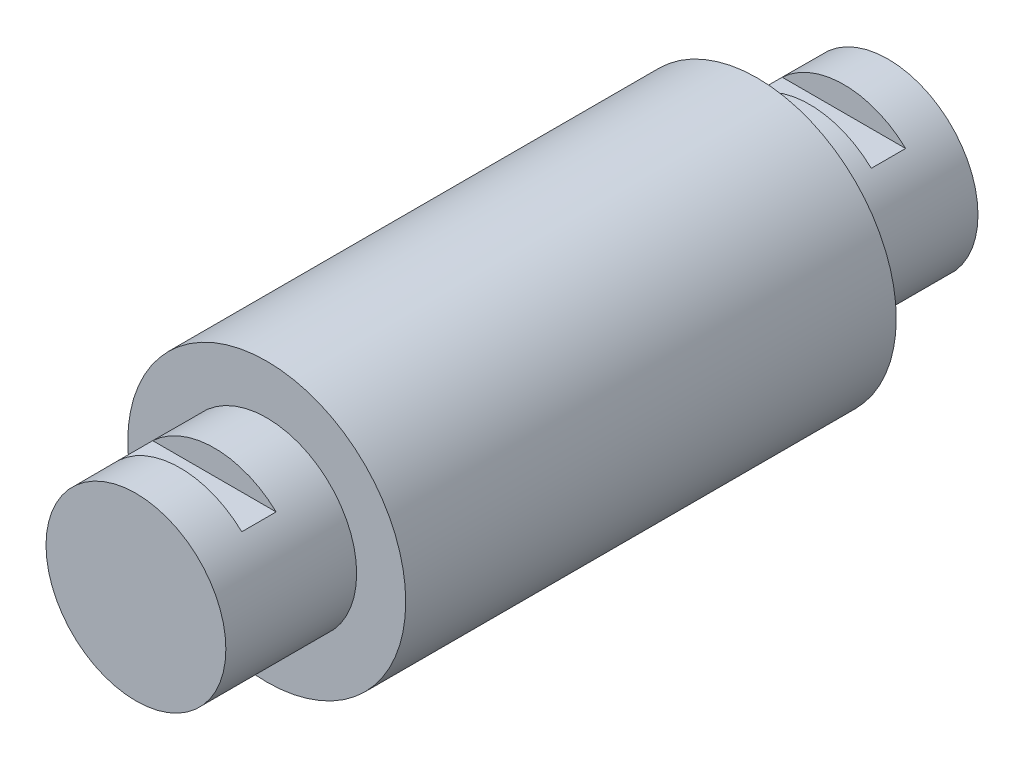
SolidWorks part; units mm, degrees
ref_plane "Front Plane" through (0, 0, 0) normal (0, 0, 1) x (1, 0, 0)
ref_plane "Top Plane" through (0, 0, 0) normal (0, 1, 0) x (1, 0, 0)
ref_plane "Right Plane" through (0, 0, 0) normal (1, 0, 0) x (0, 0, -1)
sketch "Sketch2" plane through (0, 0, 0) normal (0, 0, 1) x (1, 0, 0)
  circle A0 centre (0, 0) radius 42.5
  dimension "D1" = 85
extrude "Boss-Extrude2" add sketch "Sketch2" along normal mid plane 150 contours A0
sketch "Sketch3" plane through (0, 0, 75) normal (0, 0, 1) x (1, 0, 0)
  circle A0 centre (0, 0) radius 27.5
  dimension "D1" = 55
extrude "Boss-Extrude3" add sketch "Sketch3" along normal blind 40
sketch "Sketch4" plane through (0, 0, 0) normal (1, 0, 0) x (0, 0, -1)
  line L0 (-75, 27.5) -> (-115, 27.5) construction
  line L1 (-101.5, 28.7988) -> (-91, 28.7988)
  line L2 (-101.5, 28.7988) -> (-101.5, 20)
  line L3 (-101.5, 20) -> (-91, 20)
  line L4 (-91, 28.7988) -> (-91, 20)
  line L6 (-120.3112, 0) -> (-36.6695, 0) construction
  line L7 (-75, 42.5) -> (-75, -42.5) construction
  dimension "D1" = 7.5
  dimension "D2" = 10.5
  dimension "D3" = 20
  dimension "D4" = 16
extrude "Cut-Extrude1" cut sketch "Sketch4" against normal mid plane 100
mirror "Mirror3" about plane through (0, 0, 0) normal (0, 0, 1) of "Cut-Extrude1", "Boss-Extrude3"
